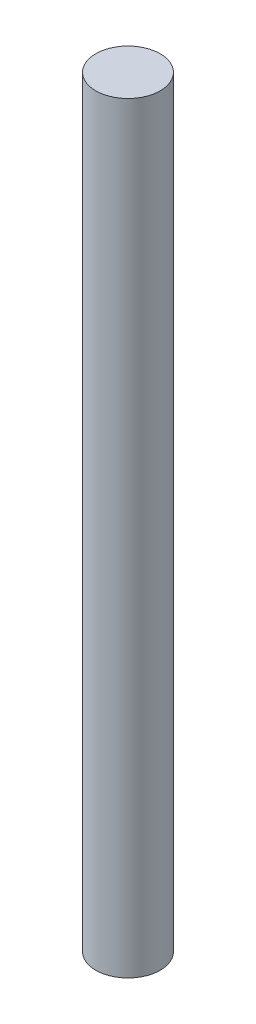
SolidWorks part; units mm, degrees
ref_plane "Front Plane" through (0, 0, 0) normal (0, 0, 1) x (1, 0, 0)
ref_plane "Top Plane" through (0, 0, 0) normal (0, 1, 0) x (1, 0, 0)
ref_plane "Right Plane" through (0, 0, 0) normal (1, 0, 0) x (0, 0, -1)
sketch "Sketch2" plane through (0, 0, 0) normal (0, 1, 0) x (1, 0, 0)
  circle A0 centre (0, 0) radius 1.985
  dimension "D1" = 3.97
extrude "Boss-Extrude1" add sketch "Sketch2" along normal blind 47
